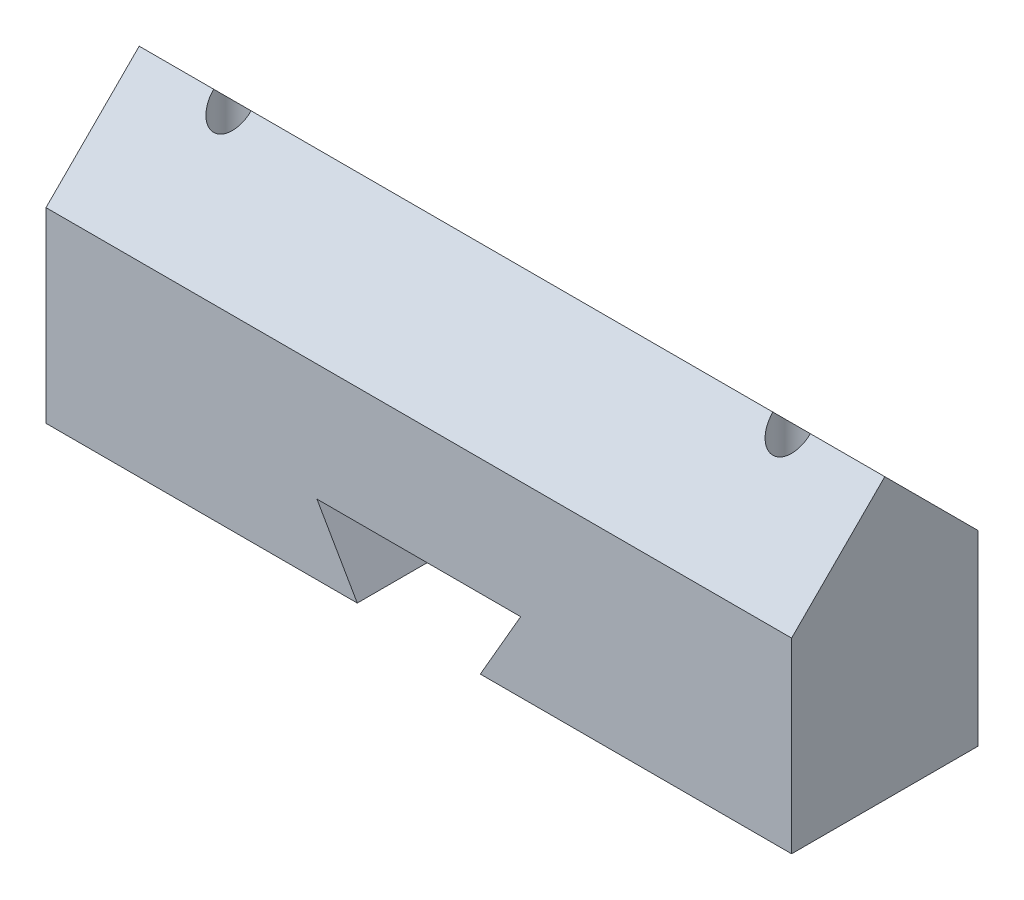
SolidWorks part; units mm, degrees
ref_plane "Front Plane" through (0, 0, 0) normal (0, 0, 1) x (1, 0, 0)
ref_plane "Top Plane" through (0, 0, 0) normal (0, 1, 0) x (1, 0, 0)
ref_plane "Right Plane" through (0, 0, 0) normal (1, 0, 0) x (0, 0, -1)
sketch "Sketch1" plane through (0, 0, 0) normal (0, 0, 1) x (1, 0, 0)
  line L0 (0, 0) -> (-5.4993, 9.525)
  line L1 (-5.4993, 9.525) -> (22.2633, 9.525)
  line L2 (22.2633, 9.525) -> (16.764, 0)
  line L3 (16.764, 0) -> (59.182, 0)
  line L4 (59.182, 0) -> (59.182, 38.1605)
  line L5 (59.182, 38.1605) -> (-42.418, 38.1605)
  line L6 (-42.418, 38.1605) -> (-42.418, 0)
  line L7 (-42.418, 0) -> (0, 0)
  dimension "D1" = 9.525
  dimension "D2" = 60
  dimension "D3" = 60
  dimension "D4" = 16.764
  dimension "D5" = 101.6
  dimension "D6" = 42.418
  dimension "D7" = 38.1605
extrude "Boss-Extrude1" add sketch "Sketch1" along normal blind 25.4
sketch "Sketch2" plane through (-42.418, 0, 0) normal (-1, 0, 0) x (0, 0, 1)
  line L0 (0, 25.4605) -> (12.7, 38.1605)
  line L1 (0, 38.1605) -> (0, 0) construction
  line L2 (25.4, 38.1605) -> (0, 38.1605) construction
  line L3 (12.7, 38.1605) -> (25.4, 25.4605)
  line L4 (25.4, 38.1605) -> (25.4, 0) construction
  line L5 (25.4, 25.4605) -> (25.4, 38.1605)
  line L6 (25.4, 38.1605) -> (0, 38.1605)
  line L7 (0, 38.1605) -> (0, 25.4605)
  line M5 (0, 38.1605) -> (0, 0)
  line M7 (25.4, 0) -> (25.4, 38.1605)
  line M8 (25.4, 38.1605) -> (0, 38.1605)
  dimension "D1" = 45
  dimension "D2" = 45
extrude "Cut-Extrude1" cut sketch "Sketch2" against normal through all contours L0 M5 M8 | L3 M8 M7
ref_plane "Plane1" through (0, 38.1605, 0) normal (0, -1, 0) x (-1, 0, 0)
hole_wizard "1/4-20 Tapped Hole1" positions "Sketch3" profile "Sketch5" tap size "1/4-20" standard "ANSI Inch"
sketch "Sketch3" plane through (0, 38.1605, 0) normal (0, -1, 0) x (-1, 0, 0)
  line L0 (-59.182, -12.7) -> (42.418, -12.7) construction
  point P0 (29.718, -12.7)
  point P4 (-46.482, -12.7)
  dimension "D1" = 12.7
  dimension "D2" = 12.7
sketch "Sketch5" plane through (-29.718, 38.1605, 12.7) normal (1, 0, 0) x (0, 0, 1)
  line L0 (0, 0) -> (0, 18.0438)
  line L1 (0, 18.0438) -> (2.5527, 16.51)
  line L2 (2.5527, 16.51) -> (2.5527, 0)
  line L5 (2.5527, 0) -> (0, 0)
  line L10 (0, 18.0438) -> (-2.5527, 16.51) construction
  line L11 (0, -6.35) -> (0, 107.95) construction
  dimension "Tap Drill Dia." = 5.1054
  dimension "Tap Drill Depth" = 16.51
  dimension "Drill Angle" = 118
